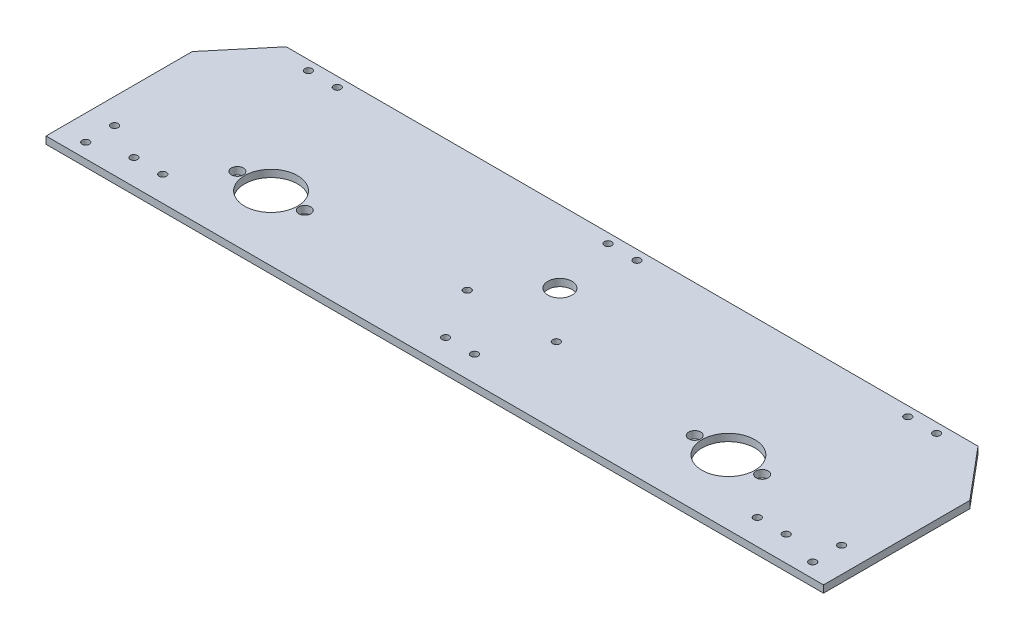
SolidWorks part; units mm, degrees
ref_plane "前视基准面" through (0, 0, 0) normal (0, 0, 1) x (1, 0, 0)
ref_plane "上视基准面" through (0, 0, 0) normal (0, 1, 0) x (1, 0, 0)
ref_plane "右视基准面" through (0, 0, 0) normal (1, 0, 0) x (0, 0, -1)
sketch "草图1" plane through (0, 0, 0) normal (0, 1, 0) x (1, 0, 0)
  line L0 (68.8945, 60.7588) -> (86.7179, 82)
  line L1 (68.8945, 0) -> (68.8945, 60.7588)
  line L2 (391.8945, 0) -> (391.8945, 60.7588)
  line L3 (86.7179, 82) -> (374.071, 82)
  line L4 (68.8945, 0) -> (391.8945, 0)
  line L5 (230.3945, 82) -> (230.3945, 0) construction
  line L6 (391.8945, 60.7588) -> (374.071, 82)
  line L7 (230.3945, 0) -> (15.3945, 0) construction
  line L8 (15.3945, -3) -> (104.8679, 103.6303) construction
  line L9 (230.3945, -3) -> (15.3945, -3) construction
  line L10 (445.3945, -3) -> (355.921, 103.6303) construction
  line L11 (230.3945, -3) -> (445.3945, -3) construction
  circle A0 centre (135.3945, 27) radius 11
  circle A1 centre (311.3945, 27) radius 2.5
  circle A2 centre (339.3945, 27) radius 2.5
  circle A3 centre (325.3945, 27) radius 11
  circle A4 centre (121.3945, 27) radius 2.5
  circle A5 centre (149.3945, 27) radius 2.5
  dimension "D4" = 22
  dimension "D7" = 50
  dimension "D10" = 5
  dimension "D2" = 82
  dimension "D3" = 323
  dimension "D5" = 27
  dimension "D6" = 3
  dimension "D8" = 28
  dimension "D9" = 14
  dimension "D11" = 215
  dimension "D12" = 161.5
  dimension "D13" = 95
extrude "凸台-拉伸1" add sketch "草图1" along normal blind 3
sketch "草图2" plane through (0, 3, 0) normal (0, 1, 0) x (1, 0, 0)
  line L0 (230.3945, 82) -> (230.3945, 0) construction
  line L1 (374.071, 82) -> (86.7179, 82) construction
  line L2 (68.8945, 0) -> (391.8945, 0) construction
  line L3 (391.8945, 0) -> (391.8945, 60.7588) construction
  circle A0 centre (236.3945, 10.5) radius 1.5
  circle A1 centre (353.8945, 10.5) radius 1.5
  circle A2 centre (365.8945, 10.5) radius 1.5
  circle A3 centre (381.3945, 6) radius 1.5
  circle A4 centre (381.3945, 18) radius 1.5
  circle A5 centre (79.3945, 18) radius 1.5
  circle A6 centre (79.3945, 6) radius 1.5
  circle A7 centre (94.8945, 10.5) radius 1.5
  circle A8 centre (106.8945, 10.5) radius 1.5
  circle A9 centre (224.3945, 10.5) radius 1.5
  dimension "D7" = 3
  dimension "D1" = 6
  dimension "D2" = 12
  dimension "D3" = 123.5
  dimension "D4" = 10.5
  dimension "D5" = 6
  dimension "D6" = 12
  dimension "D8" = 10.5
extrude "切除-拉伸1" cut sketch "草图2" against normal through all
sketch "草图3" plane through (0, 3, 0) normal (0, 1, 0) x (1, 0, 0)
  line L0 (230.3945, 82) -> (230.3945, 0) construction
  line L1 (374.071, 82) -> (86.7179, 82) construction
  line L2 (68.8945, 0) -> (391.8945, 0) construction
  circle A0 centre (248.8945, 32) radius 1.5
  circle A1 centre (211.8945, 32) radius 1.5
  dimension "D4" = 3
  dimension "D1" = 37
  dimension "D2" = 18.5
  dimension "D3" = 32
extrude "切除-拉伸2" cut sketch "草图3" against normal blind 10
extrude "切除-拉伸3" cut sketch "草图4" against normal through all
sketch "草图4" plane through (-213.1323, -49, -96.941) normal (0, -1, 0) x (1, 0, 0)
  circle A0 centre (449.5268, 18.941) radius 1.4944
  circle A1 centre (437.5268, 18.941) radius 1.5
  circle A2 centre (562.0268, 18.941) radius 1.5
  circle A3 centre (574.0268, 18.941) radius 1.5
  circle A4 centre (325.0268, 18.941) radius 1.5
  circle A5 centre (313.0268, 18.941) radius 1.5
sketch "草图6" plane through (0, 3, 0) normal (0, 1, 0) x (1, 0, 0)
  line L0 (230.3945, 82) -> (230.3945, 0) construction
  line L1 (374.071, 82) -> (86.7179, 82) construction
  line L2 (68.8945, 0) -> (391.8945, 0) construction
  circle A0 centre (230.3945, 52) radius 5
  dimension "D1" = 10
  dimension "D2" = 30
extrude "切除-拉伸5" cut sketch "草图6" against normal through all
